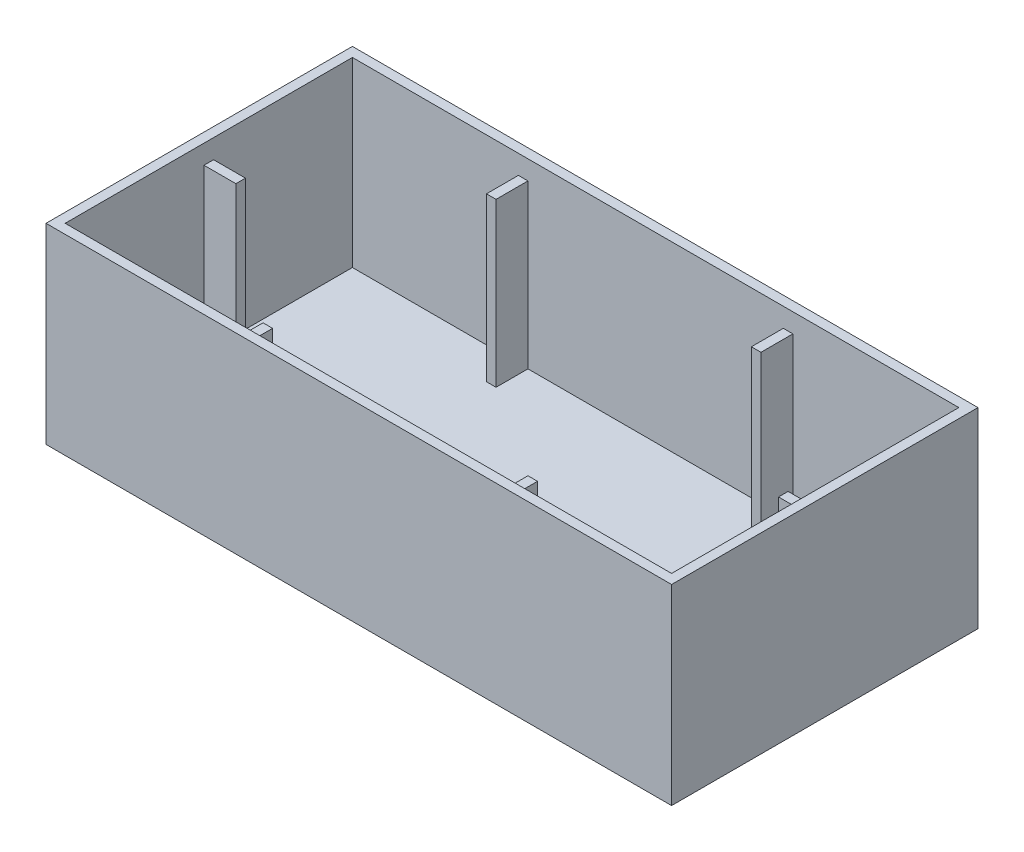
SolidWorks part; units mm, degrees
ref_plane "Front Plane" through (0, 0, 0) normal (0, 0, 1) x (1, 0, 0)
ref_plane "Top Plane" through (0, 0, 0) normal (0, 1, 0) x (1, 0, 0)
ref_plane "Right Plane" through (0, 0, 0) normal (1, 0, 0) x (0, 0, -1)
sketch "Sketch1" plane through (0, 0, 0) normal (0, 1, 0) x (1, 0, 0)
  line L1 (-49, -24) -> (49, -24)
  line L2 (-49, -24) -> (-49, 24)
  line L3 (-49, 24) -> (49, 24)
  line L4 (49, -24) -> (49, 24)
  line L5 (-49, -24) -> (49, 24) construction
  line L6 (-49, 24) -> (49, -24) construction
  point P0 (0, 0)
  dimension "D1" = 98
  dimension "D2" = 48
extrude "Boss-Extrude1" add sketch "Sketch1" along normal blind 30
shell "Shell1" thickness 1.5
sketch "Sketch2" plane through (0, 1.5, 0) normal (0, 1, 0) x (1, 0, 0)
  line L0 (47.5, 22.5) -> (-47.5, 22.5) construction
  line L1 (-21.5, 22.5) -> (-20, 22.5)
  line L2 (-21.5, 22.5) -> (-21.5, 17.5)
  line L3 (-21.5, 17.5) -> (-20, 17.5)
  line L4 (-20, 22.5) -> (-20, 17.5)
  line L6 (21.5, 22.5) -> (20, 22.5)
  line L7 (21.5, 22.5) -> (21.5, 17.5)
  line L8 (21.5, 17.5) -> (20, 17.5)
  line L9 (20, 22.5) -> (20, 17.5)
  line L10 (0, 0) -> (-42.5, 0) construction
  line L11 (20, -22.5) -> (20, -17.5)
  line L12 (21.5, -17.5) -> (20, -17.5)
  line L13 (21.5, -22.5) -> (21.5, -17.5)
  line L15 (21.5, -22.5) -> (20, -22.5)
  line L16 (-20, -22.5) -> (-20, -17.5)
  line L17 (-21.5, -17.5) -> (-20, -17.5)
  line L18 (-21.5, -22.5) -> (-21.5, -17.5)
  line L19 (42.5, 0.75) -> (42.5, -0.75)
  line L20 (47.5, -0.75) -> (42.5, -0.75)
  line L21 (47.5, 0.75) -> (47.5, -0.75)
  line L22 (47.5, 0.75) -> (42.5, 0.75)
  line L23 (-47.5, 22.5) -> (-47.5, -22.5) construction
  line L24 (-47.5, 0.75) -> (-42.5, 0.75)
  line L25 (-47.5, 0.75) -> (-47.5, -0.75)
  line L26 (-47.5, -0.75) -> (-42.5, -0.75)
  line L27 (-42.5, 0.75) -> (-42.5, -0.75)
  line L28 (0, 0) -> (0, 27.8868) construction
  line L29 (-21.5, -22.5) -> (-20, -22.5)
  point P19 (-28.6048, 0)
  point P35 (0, 0)
  dimension "D1" = 1.5
  dimension "D2" = 5
  dimension "D3" = 1.5
  dimension "D4" = 20
  dimension "D5" = 5
extrude "Boss-Extrude2" add sketch "Sketch2" along normal offset from surface (25.5 mm away) 3 up to face at (0, 30, 0)
